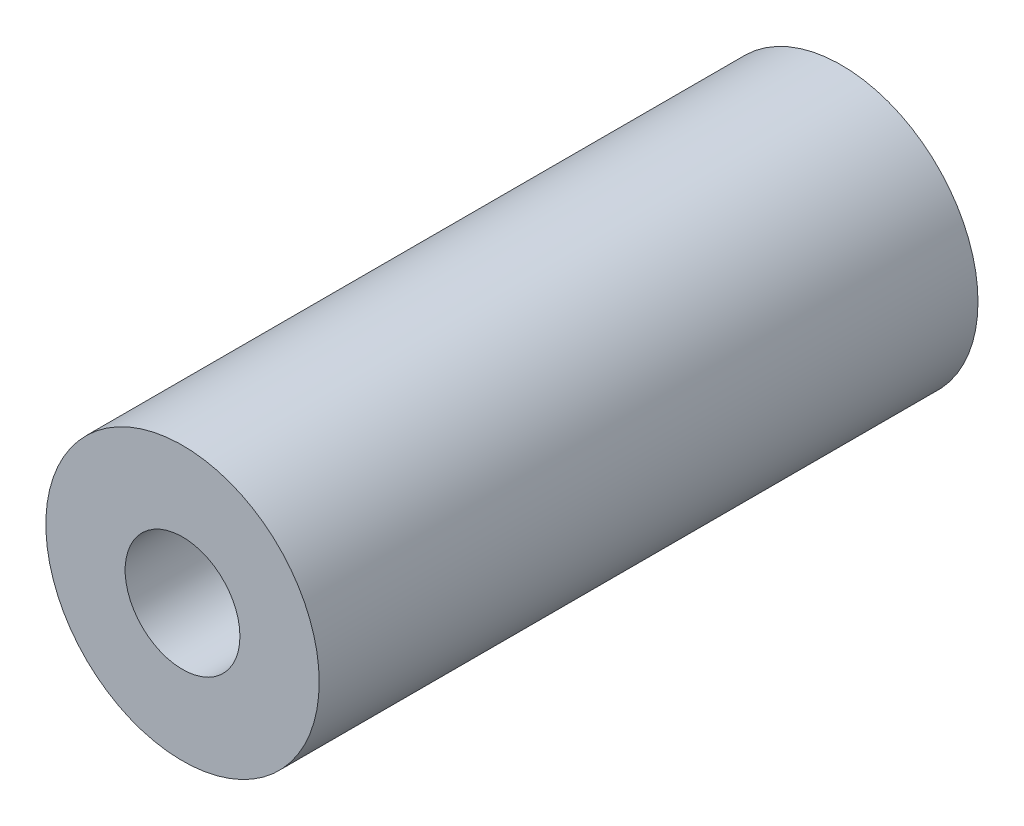
SolidWorks part; units mm, degrees
material "1060 合金"
ref_plane "正面" through (0, 0, 0) normal (0, 0, 1) x (1, 0, 0)
ref_plane "平面" through (0, 0, 0) normal (0, 1, 0) x (1, 0, 0)
ref_plane "右側面" through (0, 0, 0) normal (1, 0, 0) x (0, 0, -1)
sketch "ｽｹｯﾁ1" plane through (0, 0, 0) normal (0, 0, 1) x (1, 0, 0)
  circle A0 centre (0, 0) radius 5
  dimension "D1" = 10
extrude "ﾎﾞｽ - 押し出し1" add sketch "ｽｹｯﾁ1" along normal blind 24.1
sketch "ｽｹｯﾁ2" plane through (0, 0, 24.1) normal (0, 0, 1) x (1, 0, 0)
  circle A0 centre (0, 0) radius 2.1
  dimension "D1" = 4.2
extrude "ｶｯﾄ - 押し出し1" cut sketch "ｽｹｯﾁ2" against normal through all and the other way through all
